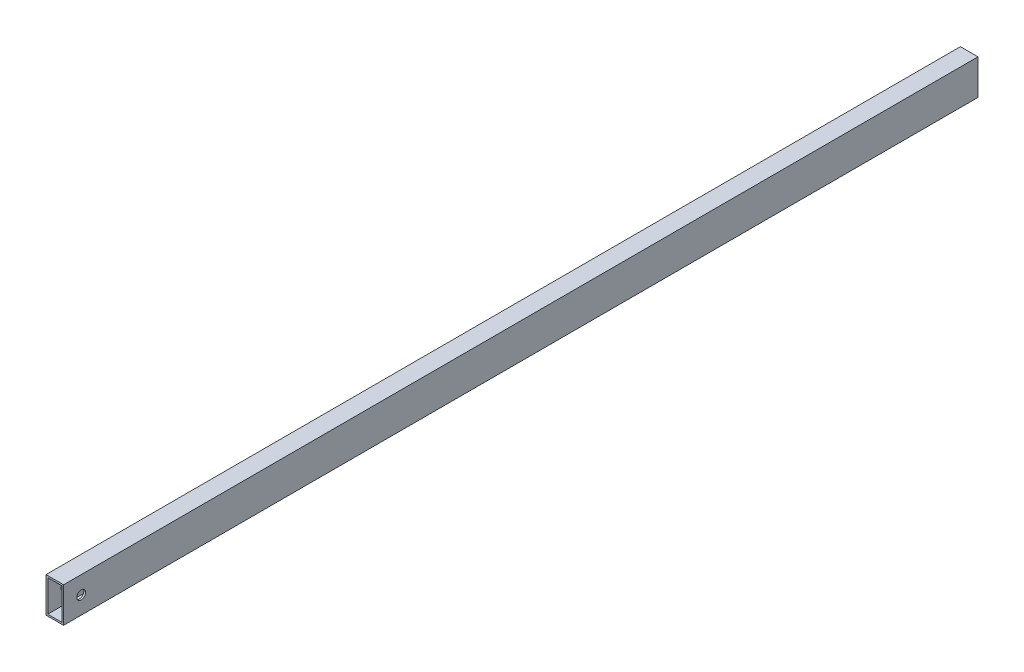
SolidWorks part; units mm, degrees
ref_plane "Front Plane" through (0, 0, 0) normal (0, 0, 1) x (1, 0, 0)
ref_plane "Top Plane" through (0, 0, 0) normal (0, 1, 0) x (1, 0, 0)
ref_plane "Right Plane" through (0, 0, 0) normal (1, 0, 0) x (0, 0, -1)
sketch "Sketch1" plane through (0, 0, 0) normal (0, 0, 1) x (1, 0, 0)
  line L0 (2.54, 48.26) -> (22.86, 48.26)
  line L1 (0, 0) -> (25.4, 0)
  line L2 (0, 0) -> (0, 50.8)
  line L3 (0, 50.8) -> (25.4, 50.8)
  line L4 (25.4, 0) -> (25.4, 50.8)
  line L5 (22.86, 2.54) -> (22.86, 48.26)
  line L6 (2.54, 2.54) -> (22.86, 2.54)
  line L7 (2.54, 2.54) -> (2.54, 48.26)
  dimension "D1" = 50.8
  dimension "D2" = 25.4
  dimension "D3" = 2.54
extrude "Boss-Extrude1" add sketch "Sketch1" along normal blind 1320.8
sketch "Sketch2" plane through (25.4, 0, 0) normal (1, 0, 0) x (0, 0, -1)
  line L0 (-1320.8, 50.8) -> (0, 50.8) construction
  line L1 (-1320.8, 0) -> (-1320.8, 50.8) construction
  circle A0 centre (-1295.4, 25.4) radius 6.35
  dimension "D1" = 12.7
  dimension "D2" = 25.4
  dimension "D3" = 25.4
extrude "Cut-Extrude1" cut sketch "Sketch2" against normal through all contours A0
